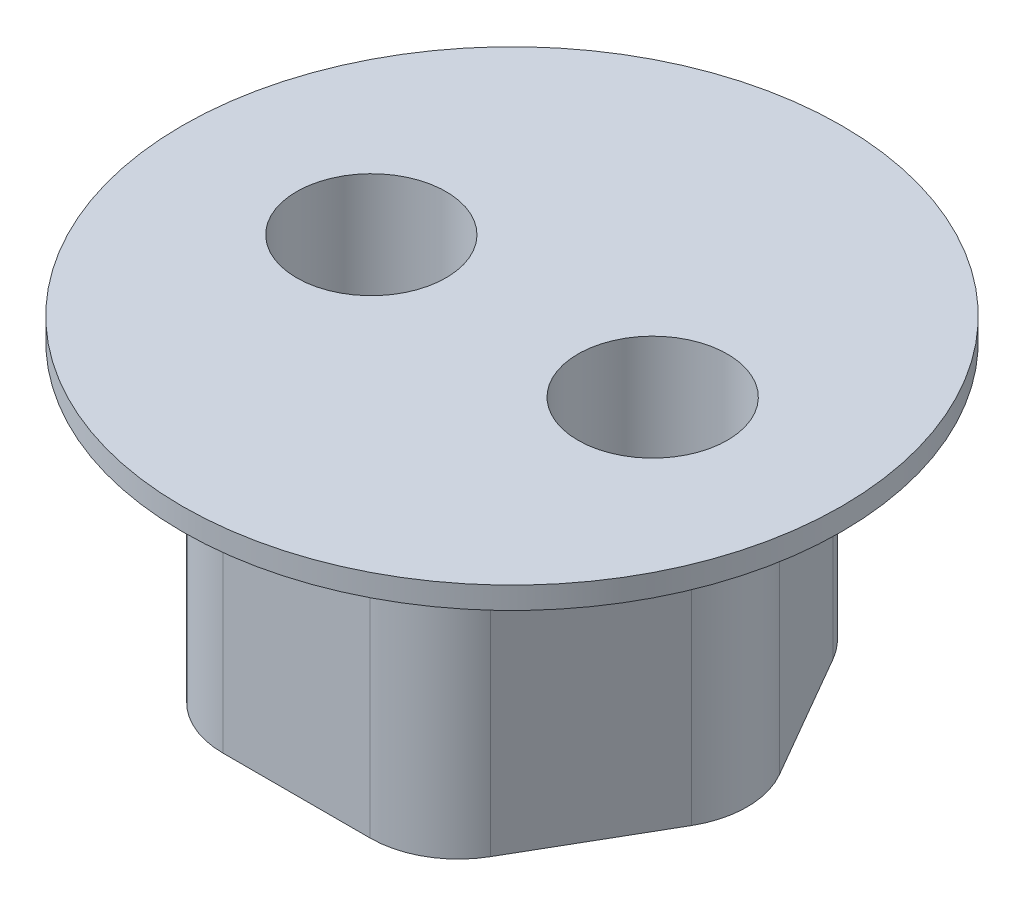
SolidWorks part; units mm, degrees
ref_plane "Front Plane" through (0, 0, 0) normal (0, 0, 1) x (1, 0, 0)
ref_plane "Top Plane" through (0, 0, 0) normal (0, 1, 0) x (1, 0, 0)
ref_plane "Right Plane" through (0, 0, 0) normal (1, 0, 0) x (0, 0, -1)
sketch "Sketch1" plane through (0, 0, 0) normal (0, 1, 0) x (1, 0, 0)
  line L1 (7.1857, 0) -> (3.5929, 6.223)
  line L2 (3.5929, 6.223) -> (-3.5929, 6.223)
  line L3 (-3.5929, 6.223) -> (-7.1857, 0)
  line L4 (-7.1857, 0) -> (-3.5929, -6.223)
  line L5 (-3.5929, -6.223) -> (3.5929, -6.223)
  line L6 (3.5929, -6.223) -> (7.1857, 0)
  circle A0 centre (0, 0) radius 6.223 construction
  dimension "D1" = 12.446
extrude "Boss-Extrude1" add sketch "Sketch1" along normal blind 8.255
sketch "Sketch2" plane through (0, 8.255, 0) normal (0, 1, 0) x (1, 0, 0)
  circle A0 centre (0, 0) radius 9.525
  dimension "D1" = 19.05
extrude "Boss-Extrude2" add sketch "Sketch2" along normal blind 0.635
sketch "Sketch3" plane through (0, 8.89, 0) normal (0, 1, 0) x (1, 0, 0)
  circle A0 centre (-4.064, 0) radius 2.159
  circle A1 centre (4.064, 0) radius 2.159
  point P6 (-4.064, 0)
  dimension "D1" = 4.318
extrude "Cut-Extrude1" cut sketch "Sketch3" against normal through all both and the other way through all
fillet "Fillet1" radius 2.54 6 edges at (3.5929, 4.1275, -6.223) (7.1857, 4.1275, 0) (3.5929, 4.1275, 6.223) (-3.5929, 4.1275, 6.223) (-3.5929, 4.1275, -6.223) (-7.1857, 4.1275, 0)
